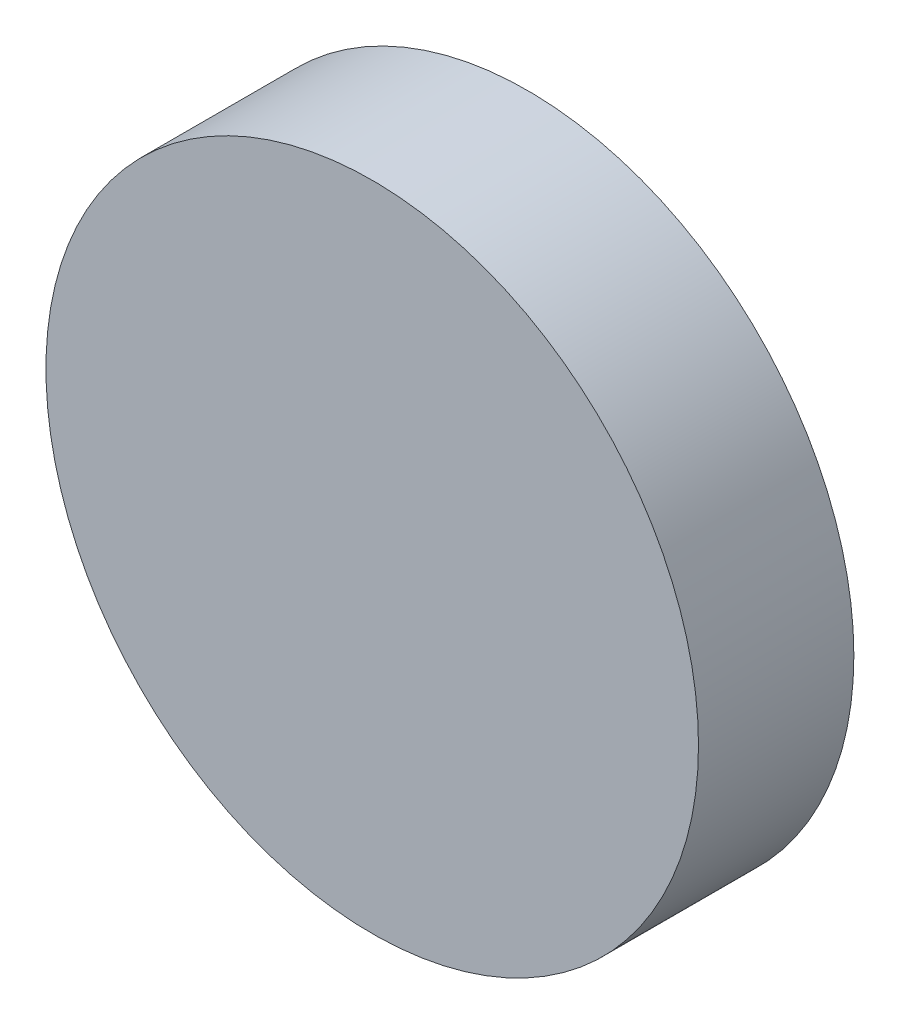
SolidWorks part; units mm, degrees
ref_plane "Plan de face" through (0, 0, 0) normal (0, 0, 1) x (1, 0, 0)
ref_plane "Plan de dessus" through (0, 0, 0) normal (0, 1, 0) x (1, 0, 0)
ref_plane "Plan de droite" through (0, 0, 0) normal (1, 0, 0) x (0, 0, -1)
sketch "Esquisse1" plane through (0, 0, 0) normal (0, 0, 1) x (1, 0, 0)
  circle A0 centre (0, 0) radius 105
  dimension "D1" = 210
extrude "Boss.-Extru.1" add sketch "Esquisse1" along normal blind 50
sketch3d "Esquisse3D1"
  line L0 (0, 0, 0) -> (0, 0, 55.2814) construction
  point P3 (0, 0, 55.2814)
sketch "Esquisse2" plane through (0, 0, 0) normal (0, 0, -1) x (-1, 0, 0)
  line L0 (0, 0) -> (0, 105) construction
  circle A0 centre (0, 0) radius 105 construction
sketch3d "Esquisse3D2"
  line L0 (0, 99.7676, 0) -> (1.5175, 104.989, 50) construction
  line L1 (0, 0, 0) -> (0, 105, 0) construction
  circle A0 centre (0, 0, 50) radius 105 construction
  point P6 (0, 0, 155)
